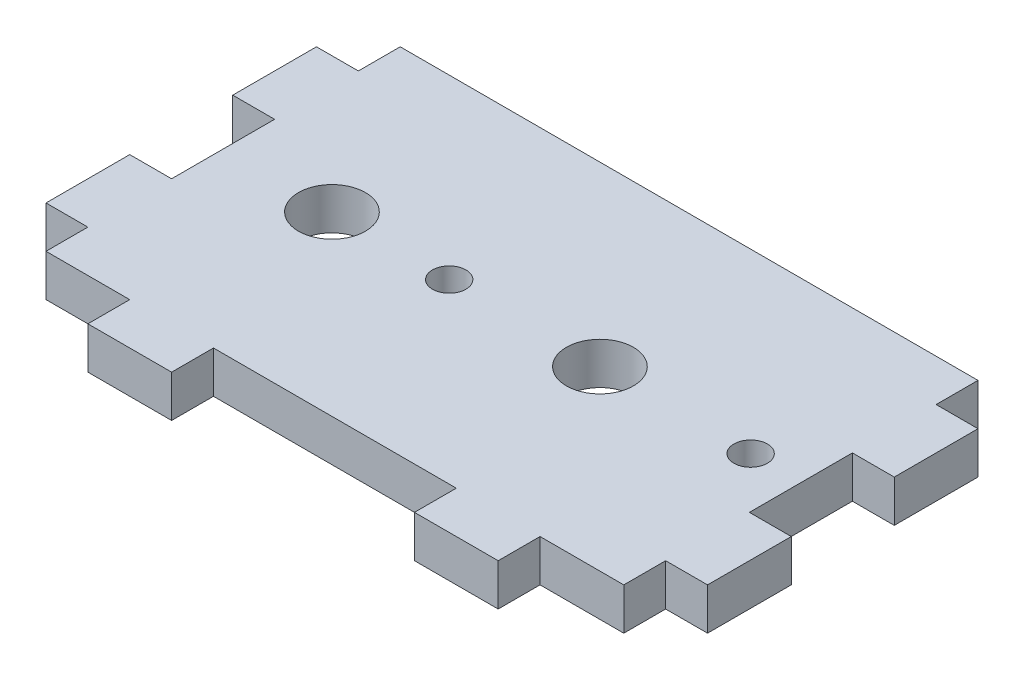
SolidWorks part; units mm, degrees
ref_plane "前视基准面" through (0, 0, 0) normal (0, 0, 1) x (1, 0, 0)
ref_plane "上视基准面" through (0, 0, 0) normal (0, 1, 0) x (1, 0, 0)
ref_plane "右视基准面" through (0, 0, 0) normal (1, 0, 0) x (0, 0, -1)
sketch "草图1" plane through (0, 0, 0) normal (0, 1, 0) x (1, 0, 0)
  line L0 (10.5, 36.242) -> (10.5, -57.7327) construction
  line L1 (-34.5, 21.15) -> (34.5, 21.15)
  line L2 (-34.5, 21.15) -> (-34.5, 16.15)
  line L3 (-34.5, -21.15) -> (-24.5, -21.15)
  line L4 (34.5, 21.15) -> (34.5, 16.15)
  line L5 (-34.5, 21.15) -> (34.5, -21.15) construction
  line L6 (-34.5, -21.15) -> (34.5, 21.15) construction
  line L7 (-21.5, 58.2535) -> (-21.5, -38.8602) construction
  line L8 (-57.7216, 0) -> (107.4697, 0) construction
  line L9 (-7.5, 23.0106) -> (-7.5, -26.9833) construction
  line L10 (28.5, -26.4595) -> (28.5, 24.208) construction
  line L11 (-34.5, 6.15) -> (-34.5, -6.15)
  line L12 (-34.5, 16.15) -> (-39.5, 16.15)
  line L13 (-34.5, -16.15) -> (-34.5, -21.15)
  line L14 (-34.5, 6.15) -> (-39.5, 6.15)
  line L15 (-39.5, 16.15) -> (-39.5, 6.15)
  line L16 (-34.5, -16.15) -> (-39.5, -16.15)
  line L17 (-14.5, -21.15) -> (14.5, -21.15)
  line L18 (-34.5, -6.15) -> (-39.5, -6.15)
  line L19 (-39.5, -16.15) -> (-39.5, -6.15)
  line L20 (34.5, 16.15) -> (39.5, 16.15)
  line L22 (34.5, 6.15) -> (39.5, 6.15)
  line L23 (39.5, 16.15) -> (39.5, 6.15)
  line L24 (34.5, -16.15) -> (39.5, -16.15)
  line L25 (34.5, 6.15) -> (34.5, -6.15)
  line L26 (34.5, -6.15) -> (39.5, -6.15)
  line L27 (39.5, -16.15) -> (39.5, -6.15)
  line L28 (24.5, -21.15) -> (34.5, -21.15)
  line L29 (-24.5, -21.15) -> (-24.5, -26.15)
  line L30 (-24.5, -26.15) -> (-14.5, -26.15)
  line L31 (-14.5, -21.15) -> (-14.5, -26.15)
  line L32 (34.5, -16.15) -> (34.5, -21.15)
  line L33 (14.5, -21.15) -> (14.5, -26.15)
  line L34 (14.5, -26.15) -> (24.5, -26.15)
  line L35 (24.5, -21.15) -> (24.5, -26.15)
  circle A0 centre (10.5, 0) radius 4
  circle A1 centre (-21.5, 0) radius 4
  circle A2 centre (-7.5, 0) radius 2
  circle A3 centre (28.5, 0) radius 2
  point P0 (0, 0)
  point P49 (34.5, -18.65)
  point P50 (-34.5, -18.65)
  point P51 (-29.5, -21.15)
  point P52 (24.5, -23.65)
  point P53 (37, 16.15)
  point P54 (-34.5, 18.65)
  dimension "D6" = 10
  dimension "D8" = 5
  dimension "D22" = 5
  dimension "D1" = 13
  dimension "D2" = 32
  dimension "D3" = 18
  dimension "D4" = 18
  dimension "D5" = 69
  dimension "D7" = 10
  dimension "D9" = 5
  dimension "D10" = 5
  dimension "D11" = 42.3
  dimension "D12" = 5
  dimension "D13" = 10
  dimension "D14" = 5
  dimension "D15" = 10
  dimension "D16" = 10
  dimension "D17" = 5
  dimension "D18" = 5
  dimension "D19" = 10
  dimension "D20" = 5
  dimension "D21" = 10
  dimension "D23" = 5
  dimension "D24" = 5
  dimension "D25" = 10
  dimension "D26" = 21.15
  dimension "D27" = 24
extrude "凸台-拉伸1" add sketch "草图1" along normal blind 5
